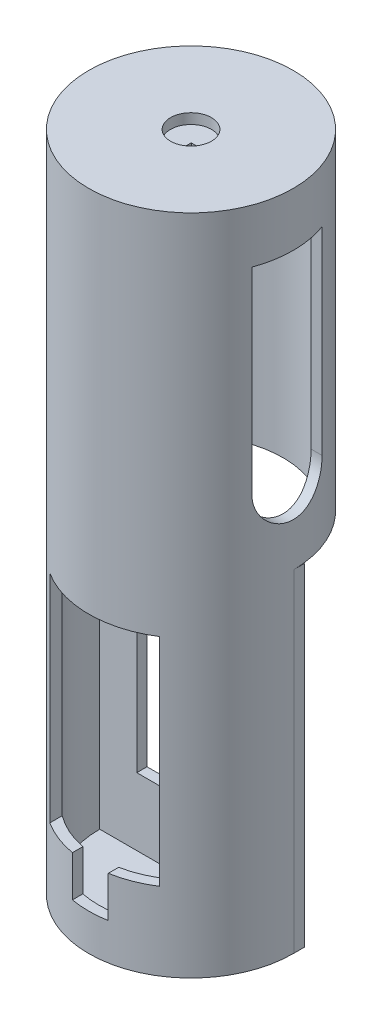
SolidWorks part; units mm, degrees
ref_plane "Front Plane" through (0, 0, 0) normal (0, 0, 1) x (1, 0, 0)
ref_plane "Top Plane" through (0, 0, 0) normal (0, 1, 0) x (1, 0, 0)
ref_plane "Right Plane" through (0, 0, 0) normal (1, 0, 0) x (0, 0, -1)
sketch "Sketch1" plane through (0, 0, 0) normal (0, 1, 0) x (1, 0, 0)
  circle A0 centre (0, 0) radius 20
  circle A1 centre (0, 0) radius 18
  dimension "D1" = 40
  dimension "D2" = 2
extrude "Boss-Extrude1" add sketch "Sketch1" along normal mid plane 130
sketch "Sketch2" plane through (0, -65, 0) normal (0, -1, 0) x (1, 0, 0)
  circle A0 centre (0, 0) radius 18
extrude "Boss-Extrude2" add sketch "Sketch2" against normal blind 2
ref_plane "Plane2" through (20, 0, 0) normal (1, 0, 0) x (0, 0, -1)
sketch "Sketch4" plane through (20, 0, 0) normal (1, 0, 0) x (0, 0, -1)
  line L0 (-20, -65) -> (20, -65) construction
  line L1 (0.15, -65) -> (24.8594, -65)
  line L2 (0.15, -65) -> (0.15, 0)
  line L3 (0.15, 0) -> (24.8594, 0)
  line L4 (24.8594, -65) -> (24.8594, 0)
  line L5 (20, -65) -> (20, 65) construction
  dimension "D1" = 65
  dimension "D2" = 19.85
extrude "Cut-Extrude1" cut sketch "Sketch4" against normal through all
sketch "Sketch5" plane through (0, 0, -0.15) normal (0, 0, -1) x (-1, 0, 0)
  line L1 (-19.9994, 0) -> (19.9994, 0)
  line L2 (-19.9994, 0) -> (-19.9994, -65)
  line L3 (-19.9994, -65) -> (19.9994, -65)
  line L4 (19.9994, 0) -> (19.9994, -65)
extrude "Boss-Extrude3" add sketch "Sketch5" along normal blind 2
sketch "Sketch6" plane through (0, 0, -2.15) normal (0, 0, -1) x (-1, 0, 0)
  line L1 (-10.75, -7.5) -> (10.75, -7.5)
  line L2 (-10.75, -7.5) -> (-10.75, -49.8)
  line L3 (-10.75, -49.8) -> (10.75, -49.8)
  line L4 (10.75, -7.5) -> (10.75, -49.8)
  line L8 (17.8711, 0) -> (-17.8711, 0) construction
  point P6 (0, -49.8)
  dimension "D1" = 7.5
  dimension "D2" = 21.5
  dimension "D3" = 42.3
extrude "Cut-Extrude2" cut sketch "Sketch6" against normal through all
sketch "Sketch7" plane through (0, 0, -2.15) normal (0, 0, -1) x (-1, 0, 0)
  line L0 (10.75, -7.5) -> (-10.75, -7.5) construction
  line L2 (0, 22) -> (0, -22) construction
  circle A0 centre (-5, -4.3) radius 1
  circle A1 centre (-5, -52.3) radius 1
  circle A2 centre (5, -52.3) radius 1
  circle A3 centre (5, -4.3) radius 1
  dimension "D1" = 2
  dimension "D2" = 2
  dimension "D3" = 48
  dimension "D4" = 3.2
  dimension "D5" = 5
extrude "Cut-Extrude3" cut sketch "Sketch7" against normal blind 2
sketch "Sketch8" plane through (0, 0, -0.15) normal (0, 0, 1) x (1, 0, 0)
  line L0 (-17.3339, -28.3) -> (15.117, -28.3) construction
  line L1 (0, -55.8) -> (0, -0.8) construction
  line L2 (0.5, -55.8) -> (0.5, -0.8)
  line L3 (-0.5, -55.8) -> (-0.5, -0.8)
  line L4 (-0.5, -0.8) -> (0.5, -0.8)
  line L5 (-0.5, -55.8) -> (0.5, -55.8)
  circle A0 centre (-5, -4.3) radius 1 construction
  point P8 (0, -28.3)
  dimension "D1" = 24
  dimension "D2" = 0.5
  dimension "55.5" = 55
  dimension "D3" = 0.5
extrude "Cut-Extrude4" cut sketch "Sketch8" against normal blind 1.5
sketch "Sketch9" plane through (0, 65, 0) normal (0, 1, 0) x (1, 0, 0)
  circle A0 centre (0, 0) radius 18
extrude "Boss-Extrude4" add sketch "Sketch9" against normal blind 2.4
sketch "Sketch10" plane through (20, 0, 0) normal (1, 0, 0) x (0, 0, -1)
  line L1 (-6.85, 54.1) -> (6.85, 54.1)
  line L2 (-6.85, 54.1) -> (-6.85, 15.35)
  line L4 (6.85, 54.1) -> (6.85, 15.35)
  line L5 (20, 65) -> (-20, 65) construction
  line L6 (0, 65) -> (0, 0) construction
  arc A0 (-6.85, 15.35) -> (6.85, 15.35) centre (0, 15.35) ccw
  point P9 (0, 54.1)
  dimension "D5" = 6.85
  dimension "D2" = 13.7
  dimension "D3" = 10.9
  dimension "D4" = 38.75
  dimension "D6" = 38.75
extrude "Cut-Extrude5" cut sketch "Sketch10" against normal through all
sketch "Sketch11" plane through (0, 54.1, 0) normal (0, -1, 0) x (1, 0, 0)
  line L0 (0, -18.5963) -> (0, 18.5963) construction
  line L1 (-6.2, -6.25) -> (-6.2, 6.25)
  line L2 (16.4, -6.25) -> (16.4, 6.25)
  line L3 (16.4, 6.25) -> (-6.2, 6.25)
  line L4 (16.4, -6.25) -> (-6.2, -6.25)
  circle A0 centre (0, 0) radius 18.5963
  dimension "D1" = 16.4
  dimension "D2" = 6.2
  dimension "D3" = 12.5
  dimension "D4" = 6.25
extrude "Boss-Extrude6" add sketch "Sketch11" against normal blind 2 contours A0 | L1 L3 L2 L4
sketch "Sketch12" plane through (0, 54.1, 0) normal (0, -1, 0) x (1, 0, 0)
  line L0 (16.4, -6.25) -> (16.4, 6.25) construction
  line L1 (-6.2, -6.25) -> (-6.2, 6.25) construction
  circle A0 centre (18.9, 0) radius 0.5
  circle A1 centre (-8.7, 0) radius 0.5
  point P8 (-6.2, 0)
  point P9 (16.4, 0)
  dimension "D1" = 1
  dimension "D3" = 1
  dimension "D2" = 2.5
  dimension "D4" = 2.5
extrude "Cut-Extrude6" cut sketch "Sketch12" against normal blind 3
sketch "Sketch15" plane through (0, 65, 0) normal (0, 1, 0) x (1, 0, 0)
  circle A0 centre (0, 0) radius 4
  dimension "D1" = 8
extrude "Cut-Extrude8" cut sketch "Sketch15" against normal blind 5
sketch "Sketch16" plane through (0, 65, 0) normal (0, 1, 0) x (1, 0, 0)
  circle A0 centre (0, 0) radius 20
extrude "Cut-Extrude9" cut sketch "Sketch16" against normal blind 0.4
sketch "Sketch18" plane through (0, 0, -0.15) normal (0, 0, 1) x (1, 0, 0)
  line L0 (10.75, -49.8) -> (-10.75, -49.8) construction
  line L1 (-3.5, -49.8) -> (3.5, -49.8)
  line L2 (-3.5, -49.8) -> (-3.5, -57.8)
  line L3 (-3.5, -57.8) -> (3.5, -57.8)
  line L4 (3.5, -49.8) -> (3.5, -57.8)
  line L5 (0, 0) -> (0, -65) construction
  point P8 (0, -49.8)
  dimension "D1" = 8
  dimension "D2" = 7
extrude "Cut-Extrude10" cut sketch "Sketch18" along normal through all
